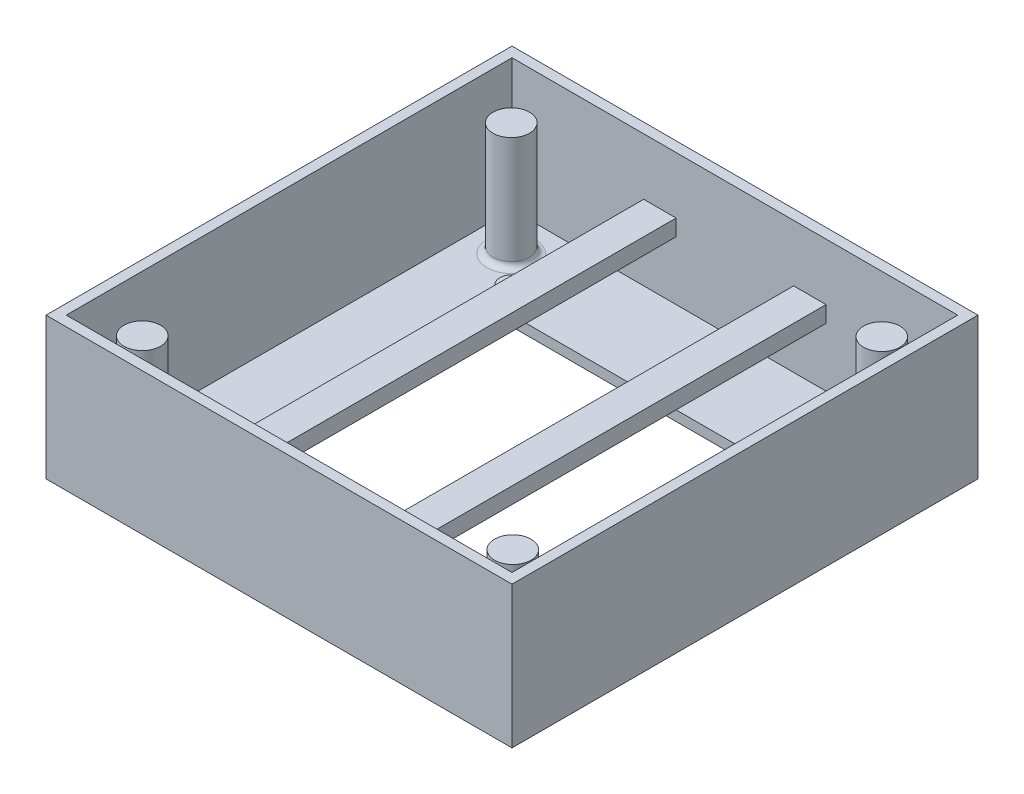
SolidWorks part; units mm, degrees
ref_plane "Front Plane" through (0, 0, 0) normal (0, 0, 1) x (1, 0, 0)
ref_plane "Top Plane" through (0, 0, 0) normal (0, 1, 0) x (1, 0, 0)
ref_plane "Right Plane" through (0, 0, 0) normal (1, 0, 0) x (0, 0, -1)
sketch "Sketch2" plane through (0, 0, 0) normal (0, 1, 0) x (1, 0, 0)
  line L1 (-57.5, 57.5) -> (57.5, 57.5)
  line L2 (-57.5, 57.5) -> (-57.5, -57.5)
  line L3 (-57.5, -57.5) -> (57.5, -57.5)
  line L4 (57.5, 57.5) -> (57.5, -57.5)
  line L5 (-57.5, 57.5) -> (57.5, -57.5) construction
  line L6 (-57.5, -57.5) -> (57.5, 57.5) construction
  point P0 (0, 0)
  dimension "D1" = 115
  dimension "D2" = 115
extrude "Boss-Extrude1" add sketch "Sketch2" along normal blind 35
shell "Shell1" thickness 2.5
sketch "Sketch3" plane through (0, 2.5, 0) normal (0, 1, 0) x (1, 0, 0)
  circle A1 centre (-45.72, -45.53) radius 3
  circle A2 centre (-45.72, -45.53) radius 3 construction
  circle A3 centre (45.72, 45.53) radius 3
  circle A4 centre (45.72, 45.53) radius 3 construction
  circle A5 centre (-45.72, 45.53) radius 3
  circle A6 centre (-45.72, 45.53) radius 3 construction
  circle A7 centre (45.72, -45.53) radius 3
  circle A8 centre (45.72, -45.53) radius 3 construction
  circle A40 centre (-45.72, -45.53) radius 4.5
  circle A41 centre (-45.72, 45.53) radius 4.5
  circle A42 centre (45.72, 45.53) radius 4.5
  circle A43 centre (45.72, -45.53) radius 4.5
  dimension "D1" = 0
  dimension "D2" = 0
  dimension "D3" = 0
  dimension "D4" = 0
  dimension "D5" = 1.5
extrude "Boss-Extrude4" add sketch "Sketch3" along normal blind 28
fillet "Fillet1" radius 1.5 1 edges at (-45.72, 2.5, 50.03)
fillet "Fillet2" radius 1.5 1 edges at (-45.72, 2.5, -41.03)
fillet "Fillet3" radius 1.5 1 edges at (45.72, 2.5, -41.03)
fillet "Fillet4" radius 1.5 1 edges at (45.72, 2.5, 50.03)
sketch "Sketch4" plane through (0, 0, 0) normal (0, -1, 0) x (1, 0, 0)
  line L1 (32.5, -32.5) -> (-32.5, -32.5)
  line L2 (32.5, -32.5) -> (32.5, 32.5)
  line L3 (32.5, 32.5) -> (-32.5, 32.5)
  line L4 (-32.5, -32.5) -> (-32.5, 32.5)
  line L5 (32.5, -32.5) -> (-32.5, 32.5) construction
  line L6 (32.5, 32.5) -> (-32.5, -32.5) construction
  point P0 (0, 0)
  dimension "D1" = 65
  dimension "D2" = 65
extrude "Cut-Extrude1" cut sketch "Sketch4" against normal through all
ref_plane "Battery_Support" through (0, 17, 0) normal (0, 1, 0) x (1, 0, 0)
sketch "Sketch5" plane through (0, 17, 0) normal (0, 1, 0) x (1, 0, 0)
  line L0 (-32.5, 32.5) -> (-32.5, -32.5) construction
  line L1 (-14.5, 56) -> (-22.5, 56)
  line L2 (-14.5, 56) -> (-14.5, -56)
  line L3 (-14.5, -56) -> (-22.5, -56)
  line L4 (-22.5, 56) -> (-22.5, -56)
  line L5 (-14.5, 56) -> (-22.5, -56) construction
  line L6 (-14.5, -56) -> (-22.5, 56) construction
  line L8 (14.5, 55.999) -> (22.5, 55.999)
  line L9 (57.5, 57.5) -> (-57.5, 57.5) construction
  line L10 (14.5, 55.999) -> (14.5, -56.001)
  line L11 (14.5, -56.001) -> (22.5, -56.001)
  line L12 (22.5, 55.999) -> (22.5, -56.001)
  line L13 (14.5, 55.999) -> (22.5, -56.001) construction
  line L14 (14.5, -56.001) -> (22.5, 55.999) construction
  line L16 (32.5, 32.5) -> (32.5, -32.5) construction
  line L18 (-57.5, -57.5) -> (57.5, -57.5) construction
  point P0 (-18.5, 0)
  point P5 (18.5, -0.001)
  dimension "D1" = 8
  dimension "D2" = 112
  dimension "D3" = 10
  dimension "D4" = 115
  dimension "D5" = 1.5
  dimension "D6" = 1.5
  dimension "D7" = 10
  dimension "D8" = 8
  dimension "D9" = 112
  dimension "D10" = 115
  dimension "D11" = 1.501
  dimension "D12" = 8
  dimension "D15" = 115
extrude "Boss-Extrude5" add sketch "Sketch5" along normal blind 4
sketch "Sketch7" plane through (0, 17, 0) normal (0, -1, 0) x (1, 0, 0)
  line L0 (32.5, -32.5) -> (32.5, 32.5) construction
  line L1 (-32.5, -32.5) -> (32.5, -32.5) construction
  line L2 (-32.5, 32.5) -> (-32.5, -32.5) construction
  circle A0 centre (-18.5, 0) radius 0.85
  circle A1 centre (18.5, 0) radius 0.85
  point P0 (18.5, 0)
  point P5 (-18.5, 0)
  dimension "D1" = 14
  dimension "D2" = 32.5
  dimension "D3" = 14
  dimension "D4" = 32.5
extrude "Cut-Extrude10" cut sketch "Sketch7" against normal blind 3
sketch "Sketch15" plane through (0, 0, 0) normal (0, -1, 0) x (1, 0, 0)
  line L0 (57.5, 57.5) -> (57.5, -57.5) construction
  line L1 (57.5, -57.5) -> (-57.5, -57.5) construction
  line L2 (-57.5, -57.5) -> (-57.5, 57.5) construction
  line L3 (-57.5, 57.5) -> (57.5, 57.5) construction
  circle A0 centre (37.5, -37.5) radius 3
  circle A1 centre (-37.5, -37.5) radius 3
  circle A2 centre (-37.5, 37.5) radius 3
  circle A3 centre (37.5, 37.5) radius 3
  dimension "D1" = 20
  dimension "D3" = 20
  dimension "D2" = 20
  dimension "D4" = 20
  dimension "D5" = 20
  dimension "D6" = 20
  dimension "D7" = 20
  dimension "D8" = 20
extrude "Boss-Extrude6" add sketch "Sketch15" against normal blind 4
